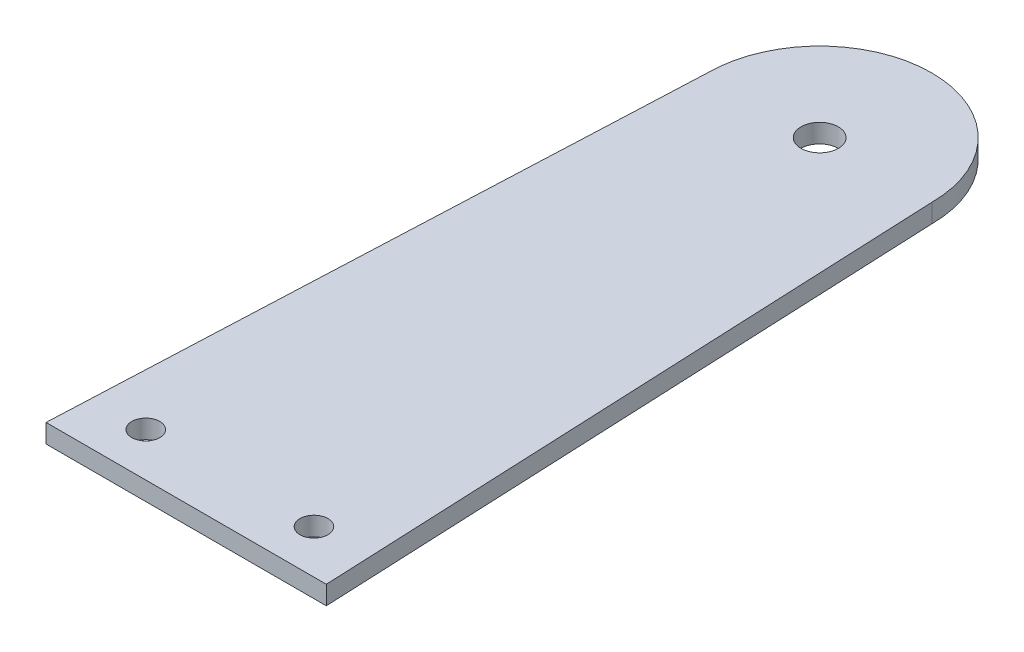
SolidWorks part; units mm, degrees
ref_plane "Спереди" through (0, 0, 0) normal (0, 0, 1) x (1, 0, 0)
ref_plane "Сверху" through (0, 0, 0) normal (0, 1, 0) x (1, 0, 0)
ref_plane "Справа" through (0, 0, 0) normal (1, 0, 0) x (0, 0, -1)
sketch "Эскиз1" plane through (0, 0, 0) normal (0, 1, 0) x (1, 0, 0)
  line L0 (-17.6252, -24.9379) -> (12.3748, -24.9379) construction
  line L1 (-17.6252, -29.6173) -> (12.3748, -29.6173)
  line L2 (-17.6252, -29.6173) -> (-17.6252, 48.1827) construction
  line L3 (-17.6252, 52.3827) -> (12.3748, 52.3827) construction
  line L5 (-11.6252, -26.4379) -> (6.3748, -26.4379) construction
  line L6 (-2.6252, -29.6173) -> (-2.6252, 60.301) construction
  line L7 (-14.6252, 38.1827) -> (-17.6252, -29.6173)
  line L8 (9.3748, 38.1827) -> (12.3748, -29.6173)
  circle A0 centre (-11.6252, -24.9379) radius 1.5
  circle A1 centre (6.3748, -24.9379) radius 1.5
  circle A2 centre (-2.6252, 38.1827) radius 2
  arc A3 (9.3748, 38.1827) -> (-14.6252, 38.1827) centre (-2.6252, 38.1827) ccw
  dimension "D3" = 67.8
  dimension "D4" = 4
  dimension "D7" = 3
  dimension "D2" = 30
  dimension "D5" = 18
  dimension "D6" = 6
extrude "Бобышка-Вытянуть1" add sketch "Эскиз1" along normal blind 2
